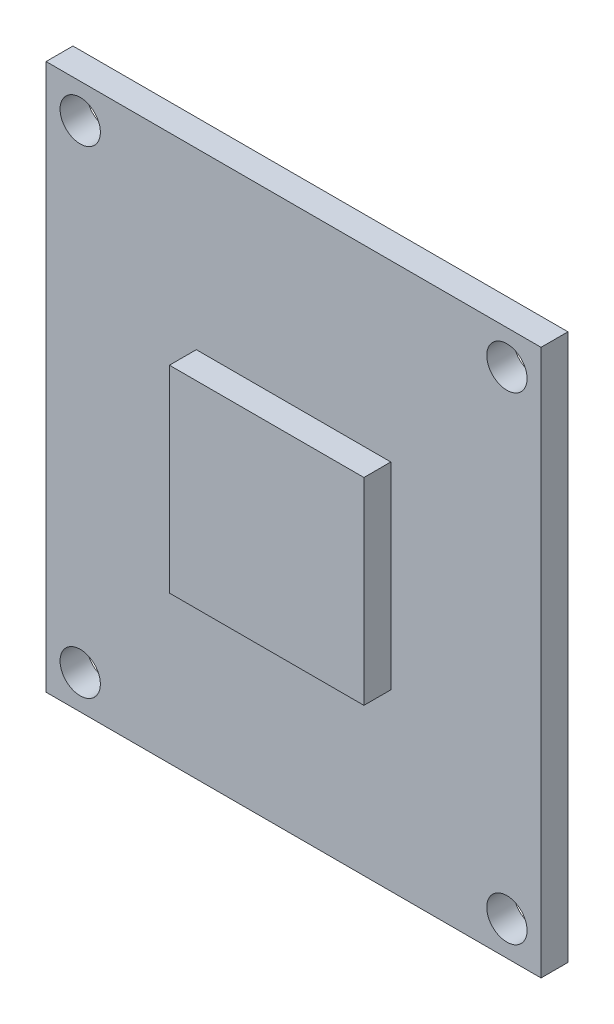
SolidWorks part; units mm, degrees
ref_plane "Front Plane" through (0, 0, 0) normal (0, 0, 1) x (1, 0, 0)
ref_plane "Top Plane" through (0, 0, 0) normal (0, 1, 0) x (1, 0, 0)
ref_plane "Right Plane" through (0, 0, 0) normal (1, 0, 0) x (0, 0, -1)
sketch "Эскиз1" plane through (0, 0, 0) normal (0, 0, 1) x (1, 0, 0)
  line L1 (-18.415, -20.32) -> (18.415, -20.32)
  line L2 (-18.415, -20.32) -> (-18.415, 20.32)
  line L3 (-18.415, 20.32) -> (18.415, 20.32)
  line L4 (18.415, -20.32) -> (18.415, 20.32)
  line L5 (-18.415, -20.32) -> (18.415, 20.32) construction
  line L6 (-18.415, 20.32) -> (18.415, -20.32) construction
  circle A0 centre (-15.875, 17.78) radius 1.5
  circle A1 centre (15.875, 17.78) radius 1.5
  circle A2 centre (-15.875, -17.78) radius 1.5
  circle A3 centre (15.875, -17.78) radius 1.5
  point P0 (0, 0)
  dimension "D7" = 3
  dimension "D8" = 3
  dimension "D13" = 3
  dimension "D14" = 3
  dimension "D1" = 36.83
  dimension "D2" = 40.64
  dimension "D3" = 2.54
  dimension "D4" = 2.54
  dimension "D5" = 2.54
  dimension "D6" = 2.54
  dimension "D9" = 2.54
  dimension "D10" = 2.54
  dimension "D11" = 2.54
  dimension "D12" = 2.54
extrude "Бобышка-Вытянуть1" add sketch "Эскиз1" along normal blind 2
sketch "Эскиз2" plane through (0, 0, 2) normal (0, 0, 1) x (1, 0, 0)
  line L1 (-7.2355, 7.3419) -> (7.2355, 7.3419)
  line L2 (-7.2355, 7.3419) -> (-7.2355, -7.3419)
  line L3 (-7.2355, -7.3419) -> (7.2355, -7.3419)
  line L4 (7.2355, 7.3419) -> (7.2355, -7.3419)
  line L5 (-7.2355, 7.3419) -> (7.2355, -7.3419) construction
  line L6 (-7.2355, -7.3419) -> (7.2355, 7.3419) construction
  point P0 (0, 0)
extrude "Бобышка-Вытянуть2" add sketch "Эскиз2" along normal blind 2
sketch "Эскиз3" plane through (0, 0, 2) normal (0, 0, 1) x (1, 0, 0)
